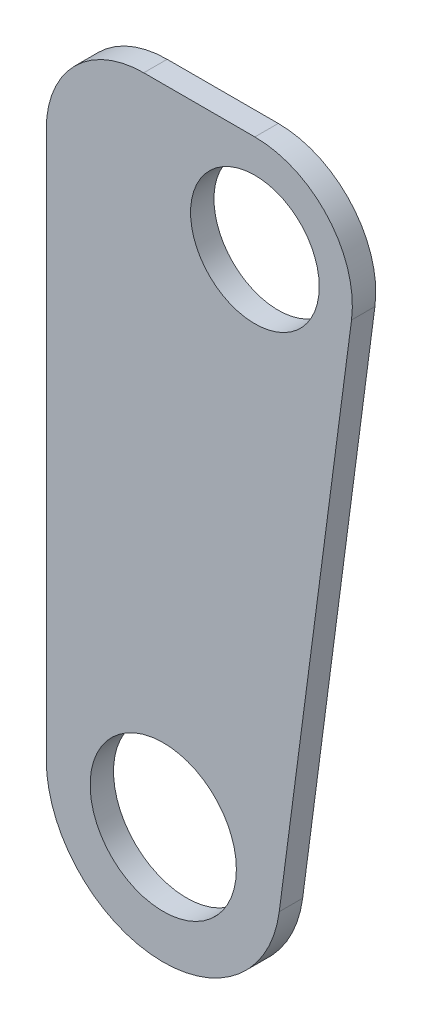
SolidWorks part; units mm, degrees
material "Q355"
ref_plane "前视基准面" through (0, 0, 0) normal (0, 0, 1) x (1, 0, 0)
ref_plane "上视基准面" through (0, 0, 0) normal (0, 1, 0) x (1, 0, 0)
ref_plane "右视基准面" through (0, 0, 0) normal (1, 0, 0) x (0, 0, -1)
sketch "草图1" plane through (0, 0, 0) normal (0, 0, 1) x (1, 0, 0)
  line L0 (0, 0) -> (-60, 0) construction
  line L1 (-60, 0) -> (-60, 330)
  line L2 (-60, 330) -> (104, 330)
  line L3 (104, 330) -> (59.4858, -7.838)
  circle A0 centre (0, 0) radius 37.5
  arc A1 (-60, 0) -> (59.4858, -7.838) centre (0, 0) ccw
  circle A2 centre (47, 280) radius 33
  dimension "D1" = 75
  dimension "D2" = 120
  dimension "D7" = 66
  dimension "D3" = 164
  dimension "D4" = 330
  dimension "D5" = 280
  dimension "D6" = 107
extrude "凸台-拉伸1" add sketch "草图1" along normal blind 12
fillet "圆角1" radius 50 2 edges at (-60, 330, 6) (104, 330, 6)
ref_plane "基准面1" through (0, 0, 0) normal (-0.9862, 0.1655, 0) x (0, 0, 1)
